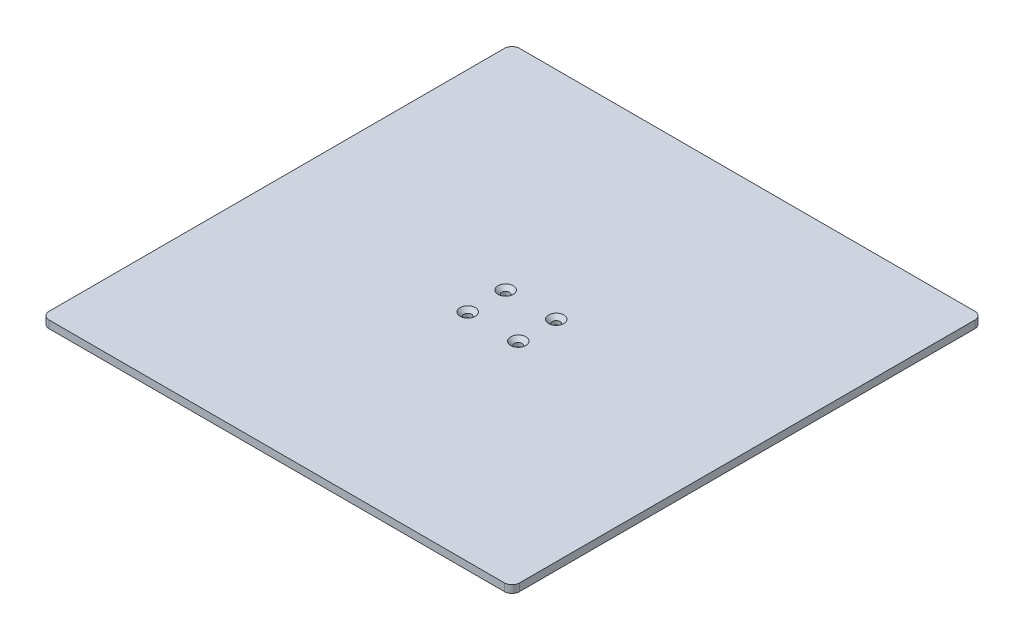
SolidWorks part; units mm, degrees
ref_plane "Front Plane" through (0, 0, 0) normal (0, 0, 1) x (1, 0, 0)
ref_plane "Top Plane" through (0, 0, 0) normal (0, 1, 0) x (1, 0, 0)
ref_plane "Right Plane" through (0, 0, 0) normal (1, 0, 0) x (0, 0, -1)
sketch "Sketch1" plane through (0, 0, 0) normal (0, 1, 0) x (1, 0, 0)
  line L1 (-93, -93) -> (93, -93)
  line L2 (-93, -93) -> (-93, 93)
  line L3 (-93, 93) -> (93, 93)
  line L4 (93, -93) -> (93, 93)
  line L5 (-93, -93) -> (93, 93) construction
  line L6 (-93, 93) -> (93, -93) construction
  point P0 (0, 0)
extrude "Boss-Extrude1" add sketch "Sketch1" against normal blind 3
fillet "Fillet1" radius 3 4 edges at (-93, -1.5, 93) (-93, -1.5, -93) (93, -1.5, -93) (93, -1.5, 93)
sketch "Sketch2" plane through (0, 0, 0) normal (0, 1, 0) x (1, 0, 0)
  circle A4 centre (-10, -7.5) radius 1.5
  circle A5 centre (-10, 7.5) radius 1.5
  circle A6 centre (10, 7.5) radius 1.5
  circle A7 centre (10, -7.5) radius 1.5
extrude "Cut-Extrude1" cut sketch "Sketch2" against normal blind 10
chamfer "Chamfer1" distance 1.5 angle 45 4 edges at (10, 0, 9) (-10, 0, 9) (-10, 0, -6) (10, 0, -6)
